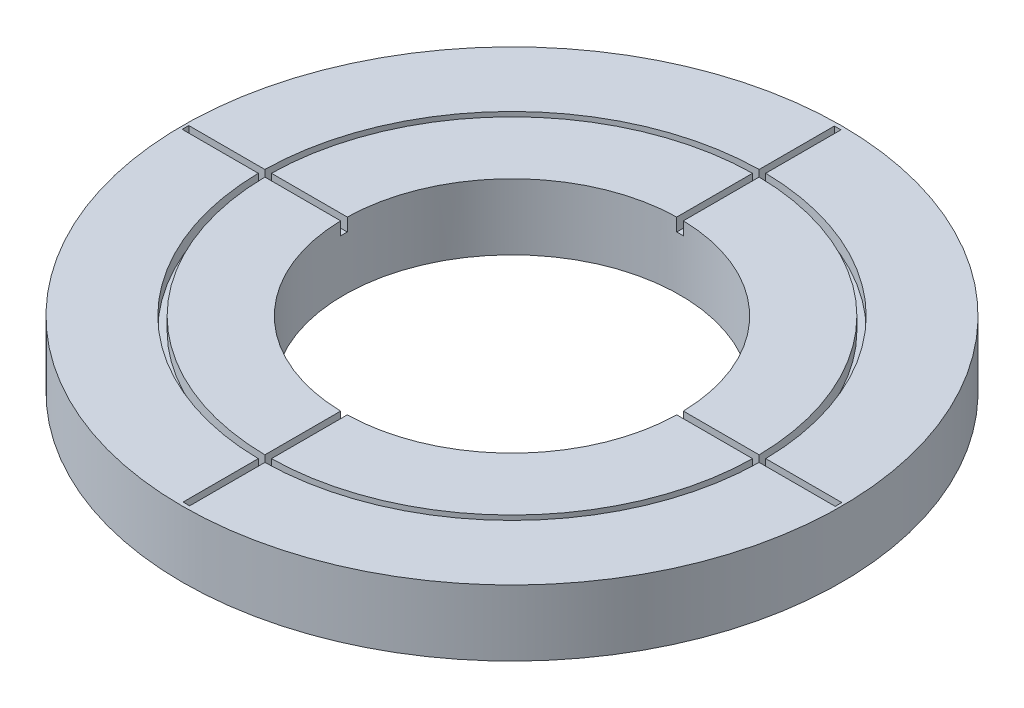
SolidWorks part; units mm, degrees
ref_plane "Front Plane" through (0, 0, 0) normal (0, 0, 1) x (1, 0, 0)
ref_plane "Top Plane" through (0, 0, 0) normal (0, 1, 0) x (1, 0, 0)
ref_plane "Right Plane" through (0, 0, 0) normal (1, 0, 0) x (0, 0, -1)
sketch "Sketch1" plane through (0, 0, 0) normal (0, 1, 0) x (1, 0, 0)
  circle A0 centre (0, 0) radius 12.7
extrude "Boss-Extrude1" add sketch "Sketch1" along normal blind 2.54
sketch "Sketch2" plane through (0, 2.54, 0) normal (0, 1, 0) x (1, 0, 0)
  circle A0 centre (0, 0) radius 6.223
  circle A1 centre (0, 0) radius 6.477
extrude "Cut-Extrude1" cut sketch "Sketch2" against normal blind 0.5
sketch "Sketch3" plane through (0, 2.54, 0) normal (0, 1, 0) x (1, 0, 0)
  circle A0 centre (0, 0) radius 3.048
  circle A1 centre (0, 0) radius 3.302
extrude "Cut-Extrude2" cut sketch "Sketch3" against normal blind 0.5
sketch "Sketch4" plane through (0, 2.54, 0) normal (0, 1, 0) x (1, 0, 0)
  circle A0 centre (0, 0) radius 0.25
extrude "Cut-Extrude3" cut sketch "Sketch4" against normal blind 0.5
sketch "Sketch5" plane through (0, 2.54, 0) normal (0, 1, 0) x (1, 0, 0)
  circle A0 centre (0, 0) radius 9.398
  circle A1 centre (0, 0) radius 9.652
extrude "Cut-Extrude4" cut sketch "Sketch5" against normal blind 0.5
sketch "Sketch6" plane through (0, 2.54, 0) normal (0, 1, 0) x (1, 0, 0)
  line L1 (-12.5828, -0.127) -> (12.5828, -0.127)
  line L2 (-12.5828, -0.127) -> (-12.5828, 0.127)
  line L3 (-12.5828, 0.127) -> (12.5828, 0.127)
  line L4 (12.5828, -0.127) -> (12.5828, 0.127)
  line L5 (-12.5828, -0.127) -> (12.5828, 0.127) construction
  line L6 (-12.5828, 0.127) -> (12.5828, -0.127) construction
  point P0 (0, 0)
  dimension "D1" = 0.254
extrude "Cut-Extrude5" cut sketch "Sketch6" against normal blind 0.5
sketch "Sketch7" plane through (0, 2.54, 0) normal (0, 1, 0) x (1, 0, 0)
  line L1 (-0.127, -12.5492) -> (0.127, -12.5492)
  line L2 (-0.127, -12.5492) -> (-0.127, 12.5492)
  line L3 (-0.127, 12.5492) -> (0.127, 12.5492)
  line L4 (0.127, -12.5492) -> (0.127, 12.5492)
  line L5 (-0.127, -12.5492) -> (0.127, 12.5492) construction
  line L6 (-0.127, 12.5492) -> (0.127, -12.5492) construction
  point P0 (0, 0)
  dimension "D1" = 0.254
extrude "Cut-Extrude6" cut sketch "Sketch7" against normal blind 0.5
sketch "Sketch8" plane through (0, 2.54, 0) normal (0, 1, 0) x (1, 0, 0)
  circle A0 centre (0, 0) radius 6.477
extrude "Cut-Extrude7" cut sketch "Sketch8" against normal blind 10
